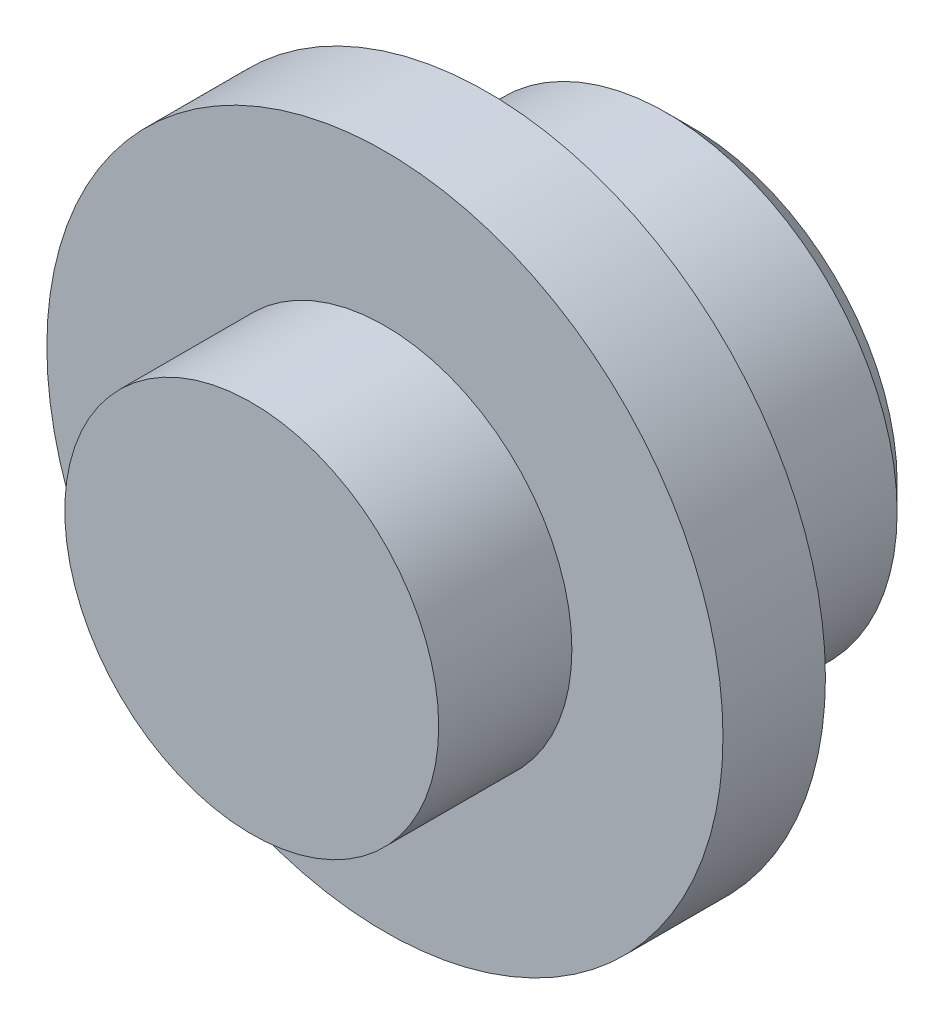
SolidWorks part; units mm, degrees
ref_plane "Front Plane" through (0, 0, 0) normal (0, 0, 1) x (1, 0, 0)
ref_plane "Top Plane" through (0, 0, 0) normal (0, 1, 0) x (1, 0, 0)
ref_plane "Right Plane" through (0, 0, 0) normal (1, 0, 0) x (0, 0, -1)
sketch "Sketch1" plane through (0, 0, 0) normal (0, 0, 1) x (1, 0, 0)
  arc A3 (-129.1615, -4.1494) -> (-129.1615, -1.9506) centre (-126.05, -3.05) ccw
  circle A4 centre (-126.05, -3.05) radius 3.3
  dimension "D1" = 0.2
extrude "Boss-Extrude2" add sketch "Sketch1" against normal up to surface (1 mm away) contours A4
sketch "Sketch4" plane through (0, 0, -1) normal (0, 0, -1) x (-1, 0, 0)
  circle A0 centre (126.05, -3.05) radius 2.25
  dimension "D1" = 4.5
extrude "Boss-Extrude3" add sketch "Sketch4" along normal blind 2
chamfer "Chamfer4" distance 0.25 angle 45 1 edges at (-128.3, -3.05, -3)
sketch "Sketch5" plane through (0, 0, 0) normal (0, 0, 1) x (1, 0, 0)
  circle A0 centre (-126.05, -3.05) radius 1.825
  dimension "D1" = 3.65
extrude "Boss-Extrude4" add sketch "Sketch5" along normal blind 1.3
